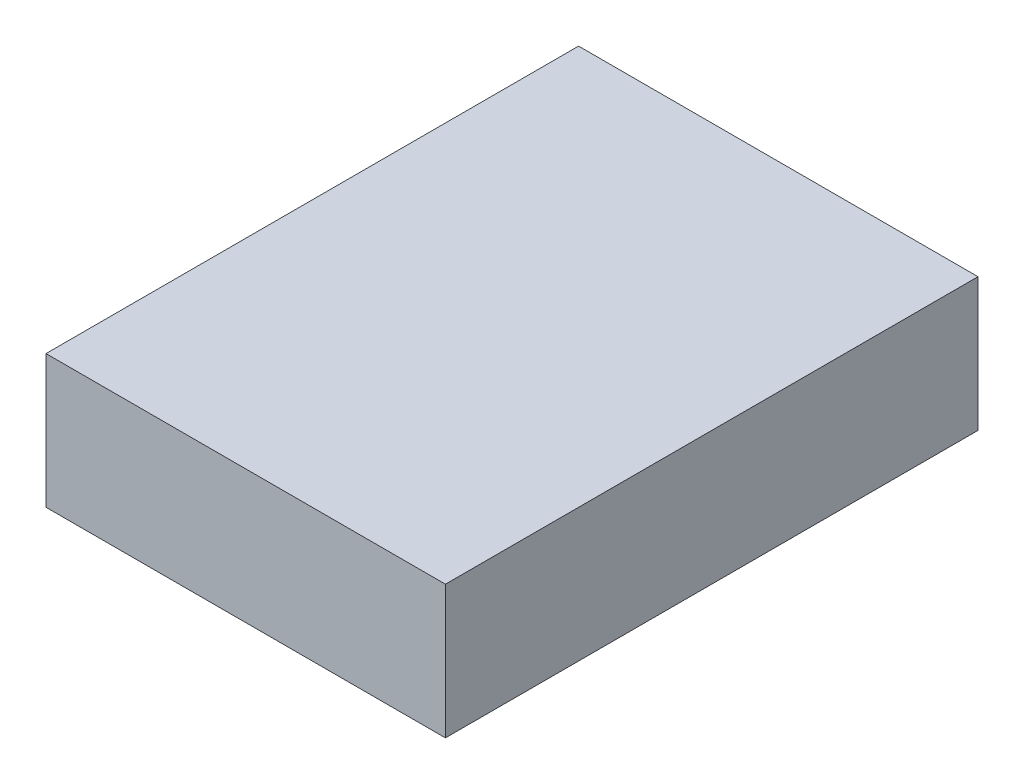
SolidWorks part; units mm, degrees
ref_plane "Front Plane" through (0, 0, 0) normal (0, 0, 1) x (1, 0, 0)
ref_plane "Top Plane" through (0, 0, 0) normal (0, 1, 0) x (1, 0, 0)
ref_plane "Right Plane" through (0, 0, 0) normal (1, 0, 0) x (0, 0, -1)
sketch "Sketch1" plane through (0, 0, 0) normal (0, 1, 0) x (1, 0, 0)
  line L1 (30, 40) -> (-30, 40)
  line L2 (30, 40) -> (30, -40)
  line L3 (30, -40) -> (-30, -40)
  line L4 (-30, 40) -> (-30, -40)
  line L5 (30, 40) -> (-30, -40) construction
  line L6 (30, -40) -> (-30, 40) construction
  point P0 (0, 0)
  dimension "D1" = 80
  dimension "D2" = 60
extrude "Boss-Extrude2" add sketch "Sketch1" along normal blind 20 contours L4 L3 L2 L1
